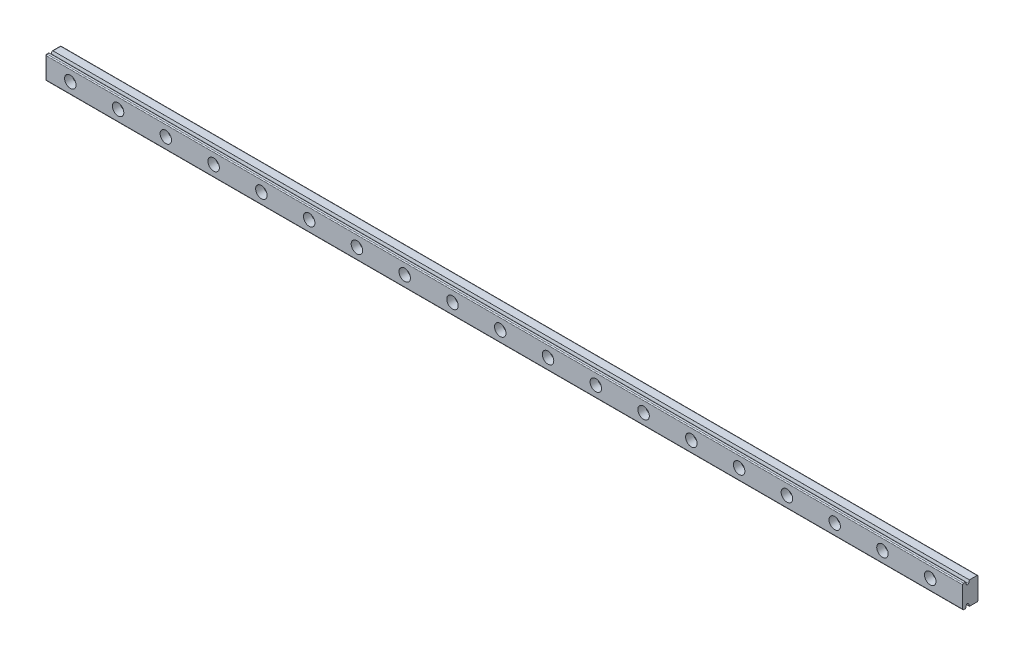
SolidWorks part; units mm, degrees
ref_plane "Front Plane" through (0, 0, 0) normal (0, 0, 1) x (1, 0, 0)
ref_plane "Top Plane" through (0, 0, 0) normal (0, 1, 0) x (1, 0, 0)
ref_plane "Right Plane" through (0, 0, 0) normal (1, 0, 0) x (0, 0, -1)
sketch "Sketch1" plane through (0, 0, 0) normal (1, 0, 0) x (0, 0, -1)
  line L0 (-0.5, 6) -> (4, 6)
  line L1 (-4, 6) -> (-2.5, 6)
  line L2 (-4, 6) -> (-4, -6)
  line L3 (-4, -6) -> (-2.5, -6)
  line L4 (4, 6) -> (4, -6)
  line L5 (-4, 6) -> (4, -6) construction
  line L6 (-4, -6) -> (4, 6) construction
  line L8 (-2.5, 6) -> (-2.5, 4.25)
  line L9 (-2.5, 4.25) -> (-0.5, 4.25)
  line L10 (-0.5, 6) -> (-0.5, 4.25)
  line L12 (-2.5, -6) -> (-2.5, -4.25)
  line L13 (-2.5, -4.25) -> (-0.5, -4.25)
  line L14 (-0.5, -6) -> (-0.5, -4.25)
  line L15 (-0.5, -6) -> (4, -6)
  point P0 (0, 0)
  dimension "D1" = 12
  dimension "D2" = 8
  dimension "D3" = 2
  dimension "D4" = 2
  dimension "D5" = 1.5
  dimension "D6" = 1.5
  dimension "D7" = 8.5
  dimension "D8" = 4.25
extrude "Boss-Extrude1" add sketch "Sketch1" along normal blind 500
sketch "Sketch2" plane through (0, 0, 4) normal (0, 0, 1) x (1, 0, 0)
  line L0 (0, 6) -> (0, -6) construction
  circle A0 centre (13, 0) radius 1.75
  circle A1 centre (38, 0) radius 1.75
  circle A2 centre (63, 0) radius 1.75
  circle A3 centre (88, 0) radius 1.75
  circle A4 centre (113, 0) radius 1.75
  circle A5 centre (138, 0) radius 1.75
  circle A6 centre (163, 0) radius 1.75
  circle A7 centre (188, 0) radius 1.75
  circle A8 centre (213, 0) radius 1.75
  circle A9 centre (238, 0) radius 1.75
  circle A10 centre (263, 0) radius 1.75
  circle A11 centre (288, 0) radius 1.75
  circle A12 centre (313, 0) radius 1.75
  circle A13 centre (338, 0) radius 1.75
  circle A14 centre (363, 0) radius 1.75
  circle A15 centre (388, 0) radius 1.75
  circle A16 centre (413, 0) radius 1.75
  circle A17 centre (438, 0) radius 1.75
  circle A18 centre (463, 0) radius 1.75
  circle A19 centre (488, 0) radius 1.75
  dimension "D1" = 3.5
  dimension "D2" = 13
  dimension "D3" = 20
extrude "Cut-Extrude1" cut sketch "Sketch2" against normal blind 10
sketch "Sketch3" plane through (0, 0, 4) normal (0, 0, 1) x (1, 0, 0)
  circle A0 centre (13, 0) radius 3
  circle A1 centre (38, 0) radius 3
  circle A2 centre (63, 0) radius 3
  circle A3 centre (88, 0) radius 3
  circle A4 centre (113, 0) radius 3
  circle A5 centre (138, 0) radius 3
  circle A6 centre (163, 0) radius 3
  circle A7 centre (188, 0) radius 3
  circle A8 centre (213, 0) radius 3
  circle A9 centre (238, 0) radius 3
  circle A10 centre (263, 0) radius 3
  circle A11 centre (288, 0) radius 3
  circle A12 centre (313, 0) radius 3
  circle A13 centre (338, 0) radius 3
  circle A14 centre (363, 0) radius 3
  circle A15 centre (388, 0) radius 3
  circle A16 centre (413, 0) radius 3
  circle A17 centre (438, 0) radius 3
  circle A18 centre (463, 0) radius 3
  circle A19 centre (488, 0) radius 3
  dimension "D1" = 6
  dimension "D2" = 20
extrude "Cut-Extrude2" cut sketch "Sketch3" against normal blind 4
chamfer "Chamfer1" distance 0.5 angle 74 4 edges at (250, -4.25, 2.5) (250, -4.25, 0.5) (250, 4.25, 2.5) (250, 4.25, 0.5)
fillet "Fillet1" radius 0.5 20 edges at (500, -6, -1.75) (500, 0, -4) (500, 6, -1.75) (500, 6, 3.25) (500, 0, 4) (500, -6, 3.25) (0, -6, 3.25) (0, -6, -1.75) (0, 0, -4) (0, 6, -1.75) (0, 6, 3.25) (0, 0, 4) (250, -4.25, 1) (250, -4.25, 2) (250, 4.25, 2) (250, 4.25, 1) (250, -6, 4) (250, 6, 4) (250, -6, -4) (250, 6, -4)
sketch "草图2" plane through (500, 0, 0) normal (1, 0, 0) x (0, 0, -1)
  line L1 (-5.2041, 7.4212) -> (7.9559, 7.4212)
  line L2 (-5.2041, 7.4212) -> (-5.2041, -8.0486)
  line L3 (-5.2041, -8.0486) -> (7.9559, -8.0486)
  line L4 (7.9559, 7.4212) -> (7.9559, -8.0486)
extrude "切除-拉伸2" cut sketch "草图2" against normal blind 20
